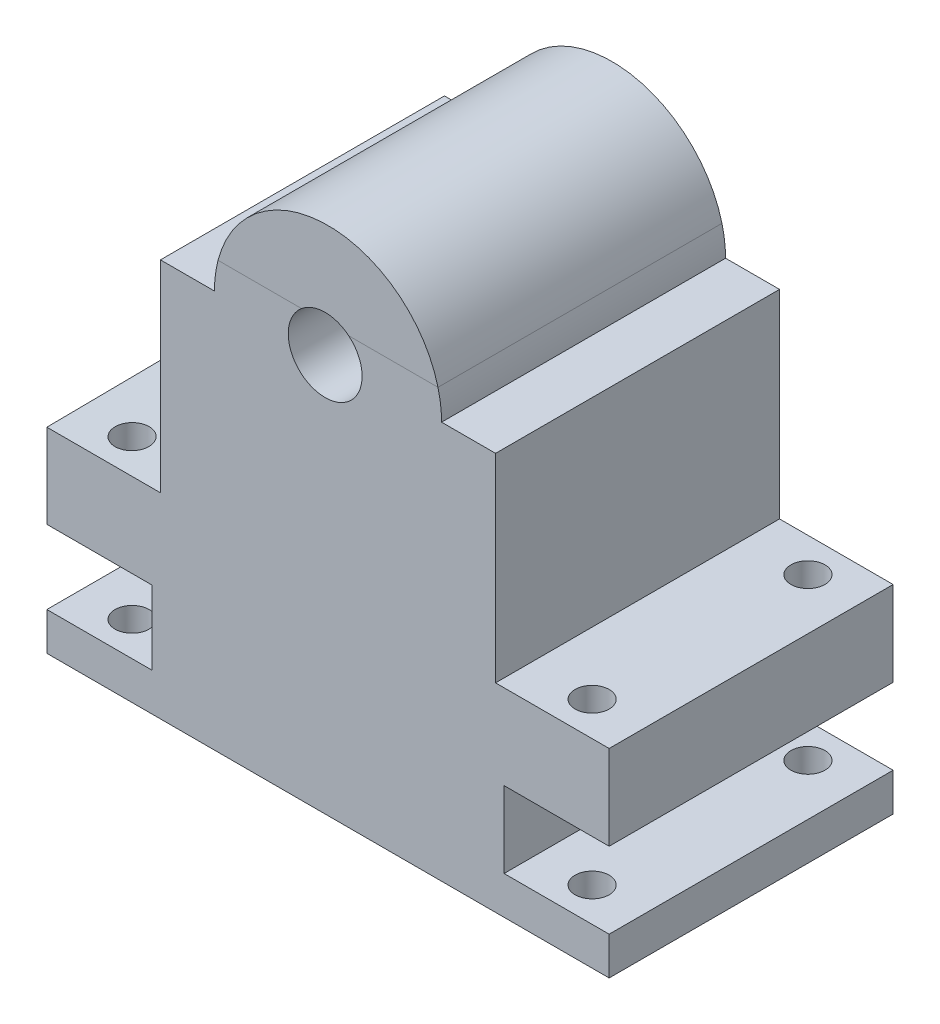
SolidWorks part; units mm, degrees
ref_plane "Plan de face" through (0, 0, 0) normal (0, 0, 1) x (1, 0, 0)
ref_plane "Plan de dessus" through (0, 0, 0) normal (0, 1, 0) x (1, 0, 0)
ref_plane "Plan de droite" through (0, 0, 0) normal (1, 0, 0) x (0, 0, -1)
sketch "Esquisse1" plane through (0, 0, 0) normal (0, 0, 1) x (1, 0, 0)
  line L0 (0, 0) -> (990, 0)
  line L1 (990, 0) -> (990, 450)
  line L2 (990, 450) -> (695, 450)
  line L3 (0, 0) -> (0, 450)
  line L4 (0, 450) -> (295, 450)
  arc A0 (695, 450) -> (295, 450) centre (495, 450) ccw
  dimension "D3" = 200
  dimension "D1" = 990
  dimension "D2" = 450
  dimension "D4" = 295
extrude "Boss.-Extru.1" add sketch "Esquisse1" along normal blind 500
sketch "Esquisse2" plane through (0, 0, 0) normal (0, -1, 0) x (1, 0, 0)
  line L0 (990, 500) -> (990, 0)
  line L1 (990, 0) -> (0, 0)
  line L2 (0, 0) -> (0, 500)
  line L3 (0, 500) -> (990, 500) construction
  line L4 (0, 500) -> (0, 0) construction
  line L5 (0, 500) -> (990, 500)
extrude "Boss.-Extru.2" add sketch "Esquisse2" along normal blind 250
sketch "Esquisse3" plane through (0, 0, 0) normal (0, 0, -1) x (-1, 0, 0)
  circle A0 centre (-490, 450) radius 65
extrude "Enlèv. mat.-Extru.1" [suppressed] cut sketch "Esquisse3" against normal blind 500
ref_plane "Plan1" through (0, 500, 0) normal (0, -1, 0) x (-1, 0, 0)
sketch "Esquisse6" [suppressed] plane through (0, 0, 500) normal (0, 0, 1) x (1, 0, 0)
  circle A0 centre (287.5, 450) radius 115
  circle A1 centre (287.5, 450) radius 65
extrude "Enlèv. mat.-Extru.4" [suppressed] cut sketch "Esquisse6" against normal blind 100
split "Fractionner2" trim tools "Plan1" bodies to split 102 resulting bodies 109 110
sketch "Esquisse7" [suppressed] plane through (0, 0, 0) normal (0, 0, -1) x (-1, 0, 0)
  circle A0 centre (-287.5, 450) radius 115
  circle A1 centre (-287.5, 450) radius 65
extrude "Enlèv. mat.-Extru.5" [suppressed] cut sketch "Esquisse7" against normal blind 100
sketch "Esquisse14" plane through (0, 0, 0) normal (-1, 0, 0) x (0, 0, 1)
  line L0 (500, 94.8716) -> (0, 100)
  line L1 (500, 450) -> (500, -250) construction
  line L2 (0, 450) -> (0, -250) construction
  line L3 (0, 100) -> (0, 450)
  line L4 (0, 450) -> (500, 450)
  line L5 (500, 450) -> (500, 94.8716)
extrude "Enlèv. mat.-Extru.6" cut sketch "Esquisse14" against normal blind 200
sketch "Esquisse15" plane through (990, 0, 0) normal (1, 0, 0) x (0, 0, -1)
  line L0 (-500, 100) -> (0, 100)
  line L1 (-500, -250) -> (-500, 450) construction
  line L2 (0, -250) -> (0, 450) construction
  line L3 (0, 100) -> (0, 450)
  line L4 (0, 450) -> (-500, 450)
  line L5 (-500, 450) -> (-500, 100)
extrude "Enlèv. mat.-Extru.7" cut sketch "Esquisse15" against normal blind 200
sketch "Esquisse16" plane through (990, 0, 0) normal (1, 0, 0) x (0, 0, -1)
  line L0 (-500, -183.1704) -> (0, -183.1704)
  line L1 (-500, -250) -> (-500, 100) construction
  line L2 (0, -250) -> (0, 100) construction
  line L3 (0, -183.1704) -> (0, -49.1291)
  line L4 (0, -49.1291) -> (-500, -49.1291)
  line L5 (-500, -49.1291) -> (-500, -183.1704)
extrude "Enlèv. mat.-Extru.8" cut sketch "Esquisse16" against normal blind 185
sketch "Esquisse17" plane through (0, 0, 0) normal (-1, 0, 0) x (0, 0, 1)
  line L0 (500, -53.29) -> (0, -53.29)
  line L1 (500, 94.8716) -> (500, -250) construction
  line L2 (0, 100) -> (0, -250) construction
  line L3 (500, -53.29) -> (500, -183.1141)
  line L4 (500, -183.1141) -> (0, -183.1141)
  line L5 (0, -183.1141) -> (0, -53.29)
extrude "Enlèv. mat.-Extru.9" cut sketch "Esquisse17" against normal blind 185
sketch "Esquisse18" plane through (0, 100, 0) normal (0, 1, 0) x (1, 0, 0)
  line L0 (990, -500) -> (990, 0) construction
  line L1 (790, -500) -> (990, -500) construction
  line L2 (790, 0) -> (990, 0) construction
  line L3 (200, -500) -> (0, -500) construction
  line L4 (0, 0) -> (0, -500) construction
  circle A0 centre (900, -440) radius 30
  circle A1 centre (900, -60) radius 30
  circle A2 centre (90, -440) radius 30
  circle A3 centre (90, -60) radius 30
  dimension "D1" = 90
  dimension "D3" = 60
  dimension "D4" = 60
  dimension "D2" = 60
  dimension "D5" = 90
extrude "Enlèv. mat.-Extru.10" cut sketch "Esquisse18" against normal blind 450
sketch "Esquisse19" plane through (0, 0, 0) normal (0, 0, -1) x (-1, 0, 0)
  circle A0 centre (-490, 450) radius 65
extrude "Enlèv. mat.-Extru.11" cut sketch "Esquisse19" against normal blind 500
